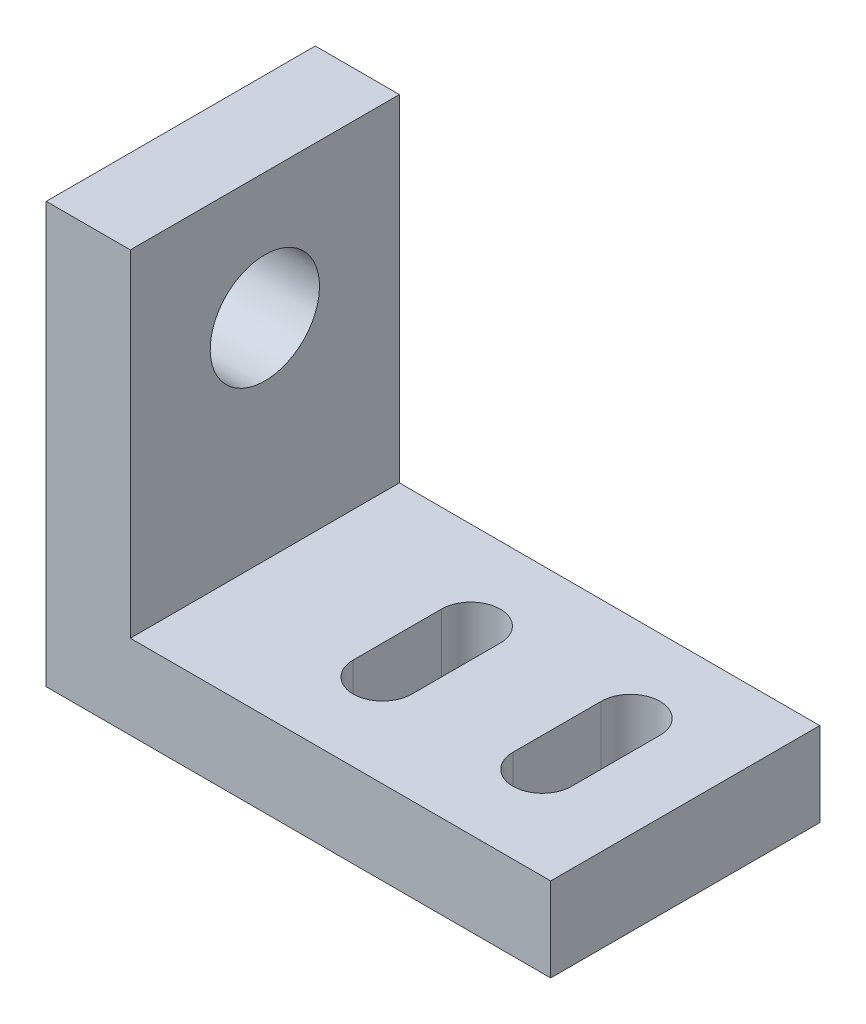
SolidWorks part; units mm, degrees
ref_plane "Piano frontale" through (0, 0, 0) normal (0, 0, 1) x (1, 0, 0)
ref_plane "Piano superiore" through (0, 0, 0) normal (0, 1, 0) x (1, 0, 0)
ref_plane "Piano destro" through (0, 0, 0) normal (1, 0, 0) x (0, 0, -1)
sketch "Schizzo1" plane through (0, 0, 0) normal (0, 0, 1) x (1, 0, 0)
  line L0 (0, 20) -> (0, 0)
  line L1 (-5, 20) -> (-5, -5)
  line L2 (0, 0) -> (25, 0)
  line L3 (-5, 20) -> (0, 20)
  line L4 (-5, -5) -> (25, -5)
  line L5 (25, 0) -> (25, -5)
  line L7 (-5, 64.0612) -> (-5, -67.6051) construction
  line L8 (0, 64.0612) -> (0, -67.6051) construction
  line L9 (-34.0975, 0) -> (67.4475, 0) construction
  line L10 (-34.0975, 20) -> (67.4475, 20) construction
  line L11 (25, 64.0612) -> (25, -67.6051) construction
  line L12 (-34.0975, -5) -> (67.4475, -5) construction
  dimension "D1" = 5
  dimension "D2" = 20
  dimension "D3" = 5
  dimension "D4" = 25
extrude "Estrusione-Estrusione1" add sketch "Schizzo1" along normal blind 16
sketch "Schizzo2" plane through (0, 0, 0) normal (1, 0, 0) x (0, 0, -1)
  line L0 (-8, 20.8039) -> (-8, 2.8239) construction
  line L1 (0.939, 20) -> (-22.5132, 20) construction
  line L2 (0.939, 12.5) -> (-22.5132, 12.5) construction
  circle A0 centre (-8, 12.5) radius 3.25
  dimension "D1" = 7.5
extrude "Taglio-Estrusione1" cut sketch "Schizzo2" against normal blind 4
sketch "Schizzo3" plane through (0, 0, 0) normal (0, 1, 0) x (1, 0, 0)
  line L0 (27.7862, 0) -> (8.0584, 0) construction
  line L1 (25, 0) -> (0, 0) construction
  line L2 (19, 0) -> (19, -20.0541) construction
  line L3 (9.5, 0) -> (9.5, -20.0541) construction
  line L4 (27.7862, -7) -> (8.0584, -7) construction
  line L5 (17.25, -5.25) -> (17.25, -10.5)
  line L6 (20.75, -5.25) -> (20.75, -10.5)
  line L7 (7.75, -5.25) -> (7.75, -10.5)
  line L8 (11.25, -5.25) -> (11.25, -10.5)
  line L10 (7.75, 0) -> (7.75, -20.0541) construction
  line L11 (11.25, 0) -> (11.25, -20.0541) construction
  line L12 (17.25, 0) -> (17.25, -20.0541) construction
  line L13 (20.75, 0) -> (20.75, -20.0541) construction
  arc A2 (20.75, -5.25) -> (17.25, -5.25) centre (19, -5.25) ccw
  arc A3 (11.25, -5.25) -> (7.75, -5.25) centre (9.5, -5.25) ccw
  arc A4 (7.75, -10.5) -> (11.25, -10.5) centre (9.5, -10.5) ccw
  arc A5 (17.25, -10.5) -> (20.75, -10.5) centre (19, -10.5) ccw
  dimension "D1" = 7
  dimension "D2" = 1.75
  dimension "D3" = 9.5
  dimension "D4" = 1.75
  dimension "D5" = 1.75
  dimension "D6" = 1.75
extrude "Taglio-Estrusione2" cut sketch "Schizzo3" against normal blind 4
sketch "Schizzo4" plane through (-4, 0, 0) normal (1, 0, 0) x (0, 0, -1)
  circle A0 centre (-8, 12.5) radius 3.25
extrude "Taglio-Estrusione3" cut sketch "Schizzo4" against normal blind 3
sketch "Schizzo5" plane through (0, -4, 0) normal (0, 1, 0) x (1, 0, 0)
  line L0 (9.5, -5.25) -> (9.5, -10.5) construction
  line L1 (11.269, -5.25) -> (11.269, -10.5)
  line L2 (7.731, -5.25) -> (7.731, -10.5)
  line L3 (19.0005, -5.25) -> (19.0005, -10.5) construction
  line L4 (20.7695, -5.25) -> (20.7695, -10.5)
  line L5 (17.2315, -5.25) -> (17.2315, -10.5)
  arc A0 (11.269, -5.25) -> (7.731, -5.25) centre (9.5, -5.25) ccw
  arc A1 (7.731, -10.5) -> (11.269, -10.5) centre (9.5, -10.5) ccw
  arc A2 (20.7695, -5.25) -> (17.2315, -5.25) centre (19.0005, -5.25) ccw
  arc A3 (17.2315, -10.5) -> (20.7695, -10.5) centre (19.0005, -10.5) ccw
  point P4 (9.5, -7.875)
  point P11 (19.0005, -7.875)
extrude "Taglio-Estrusione5" cut sketch "Schizzo5" against normal blind 3
